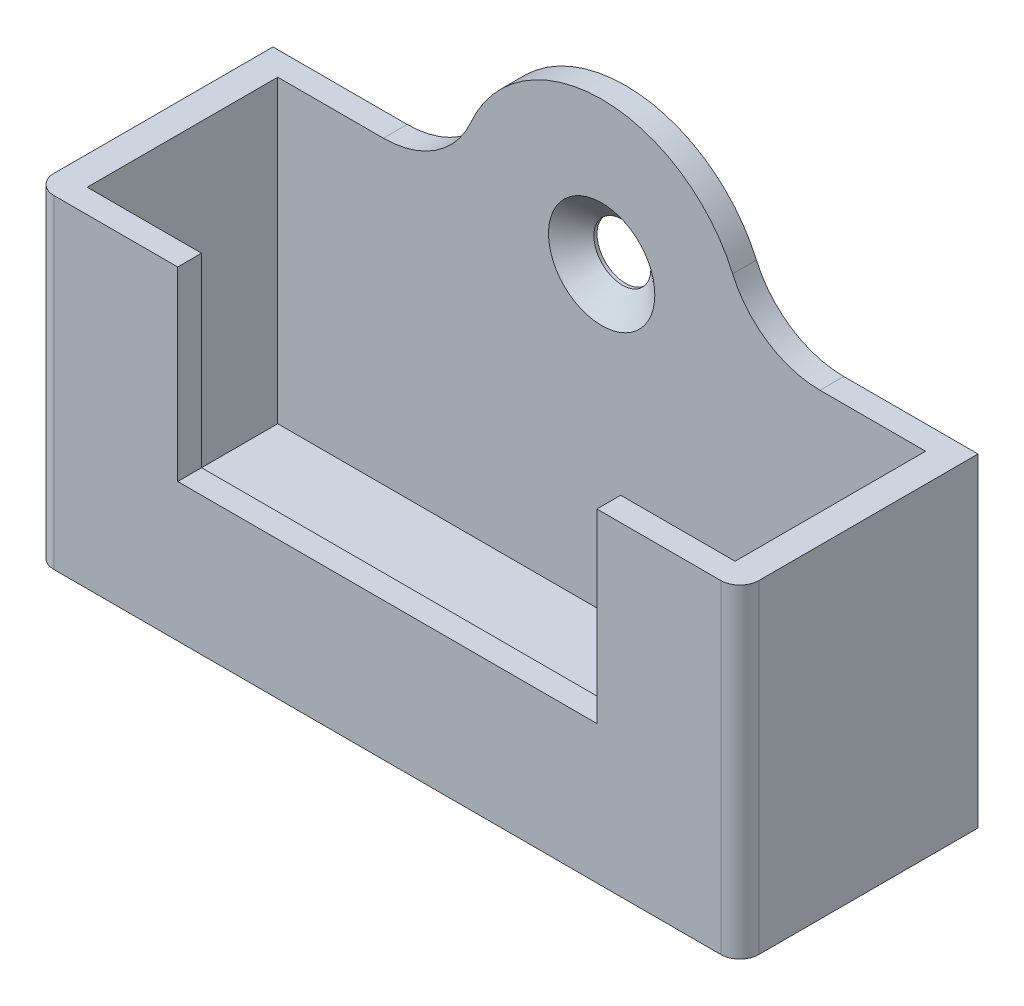
SolidWorks part; units mm, degrees
ref_plane "Front Plane" through (0, 0, 0) normal (0, 0, 1) x (1, 0, 0)
ref_plane "Top Plane" through (0, 0, 0) normal (0, 1, 0) x (1, 0, 0)
ref_plane "Right Plane" through (0, 0, 0) normal (1, 0, 0) x (0, 0, -1)
sketch "Sketch1" plane through (0, 0, 0) normal (0, 1, 0) x (1, 0, 0)
  line L1 (23.495, 7.9375) -> (-23.495, 7.9375)
  line L2 (23.495, 7.9375) -> (23.495, -7.9375)
  line L3 (23.495, -7.9375) -> (-23.495, -7.9375)
  line L4 (-23.495, 7.9375) -> (-23.495, -7.9375)
  line L5 (23.495, 7.9375) -> (-23.495, -7.9375) construction
  line L6 (23.495, -7.9375) -> (-23.495, 7.9375) construction
  point P0 (0, 0)
  dimension "D1" = 15.875
  dimension "D2" = 46.99
extrude "Boss-Extrude1" add sketch "Sketch1" along normal blind 21.59
sketch "Sketch2" plane through (0, 21.59, 0) normal (0, 1, 0) x (1, 0, 0)
  line L0 (-23.495, -7.9375) -> (23.495, -7.9375) construction
  line L1 (-21.59, -6.35) -> (21.59, -6.35)
  line L2 (-21.59, -6.35) -> (-21.59, 6.35)
  line L3 (-21.59, 6.35) -> (21.59, 6.35)
  line L4 (21.59, -6.35) -> (21.59, 6.35)
  line L5 (-21.59, -6.35) -> (21.59, 6.35) construction
  line L6 (-21.59, 6.35) -> (21.59, -6.35) construction
  line L7 (-13.97, -9.525) -> (13.97, -9.525)
  line L8 (-13.97, -9.525) -> (-13.97, -6.35)
  line L9 (-13.97, -6.35) -> (13.97, -6.35)
  line L10 (13.97, -9.525) -> (13.97, -6.35)
  line L11 (-13.97, -9.525) -> (13.97, -6.35) construction
  line L12 (-13.97, -6.35) -> (13.97, -9.525) construction
  point P0 (0, 0)
  point P6 (0, -7.9375)
  line M2 (-23.495, -7.9375) -> (23.495, -7.9375)
  dimension "D1" = 12.7
  dimension "D2" = 43.18
  dimension "D3" = 7.62
extrude "Cut-Extrude1" cut sketch "Sketch2" against normal offset from surface (20.0025 mm away) 1.5875 contours L1 L4 L3 L2 | L10 L1 L8 M2 up to face at (0, 0, 0)
sketch "Sketch3" plane through (0, 0, -6.35) normal (0, 0, 1) x (1, 0, 0)
  line L0 (-21.59, 21.59) -> (21.59, 21.59) construction
  circle A0 centre (0, 21.59) radius 9.525
  dimension "D1" = 19.05
extrude "Boss-Extrude2" add sketch "Sketch3" against normal up to surface (1.5875 mm away) up to face at (0, 10.795, -7.9375)
sketch "Sketch4" plane through (0, 0, -6.35) normal (0, 0, 1) x (1, 0, 0)
  circle A0 centre (0, 21.59) radius 9.525 construction
hole_wizard "CSK for #6 Flat Head Machine Screw (100)1" positions "Sketch6" profile "Sketch7" countersink size "#6" standard "ANSI Inch" end condition through all
sketch "Sketch6" plane through (0, 0, -6.35) normal (0, 0, 1) x (1, 0, 0)
  point P0 (0, 21.59)
sketch "Sketch7" plane through (0, 21.59, -6.35) normal (1, 0, 0) x (0, -1, 0)
  line L0 (0, 0) -> (0, 1.5875)
  line L1 (0, 1.5875) -> (1.8986, 1.5875)
  line L2 (1.8986, 1.5875) -> (1.8986, 1.38)
  line L3 (1.8986, 1.38) -> (3.5433, 0)
  line L5 (3.5433, 0) -> (0, 0)
  line L6 (-1.8986, 1.38) -> (-3.5433, 0) construction
  line L11 (0, -6.35) -> (0, 107.95) construction
  dimension "Thru Hole Dia." = 3.7973
  dimension "Thru Hole Depth" = 1.5875
  dimension "Near C'Sink Dia." = 7.0866
  dimension "Near C'Sink Angle" = 100
fillet "Fillet1" radius 6.35 2 edges at (9.525, 21.59, -7.1438) (-9.525, 21.59, -7.1438)
fillet "Fillet2" radius 1.27 2 edges at (23.495, 10.795, 7.9375) (-23.495, 10.795, 7.9375)
sketch "Sketch9" plane through (0, 1.5875, 0) normal (0, 1, 0) x (1, 0, 0)
  line L1 (-13.97, -7.9375) -> (13.97, -7.9375)
  line L2 (-13.97, -7.9375) -> (-13.97, -6.35)
  line L3 (-13.97, -6.35) -> (13.97, -6.35)
  line L4 (13.97, -7.9375) -> (13.97, -6.35)
extrude "Boss-Extrude3" add sketch "Sketch9" along normal blind 7.62
